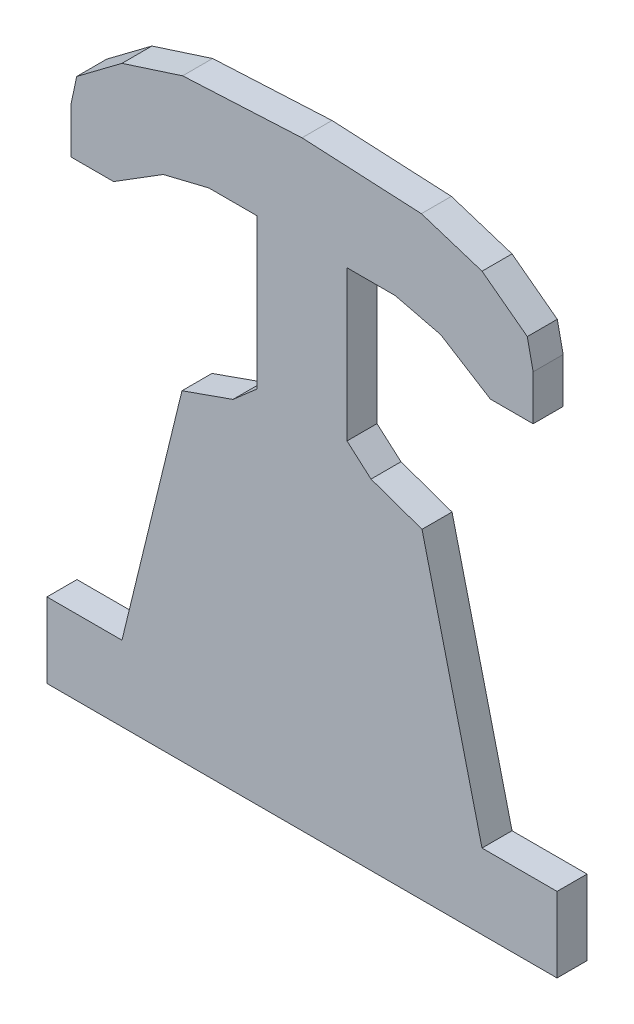
SolidWorks part; units mm, degrees
ref_plane "Front Plane" through (0, 0, 0) normal (0, 0, 1) x (1, 0, 0)
ref_plane "Top Plane" through (0, 0, 0) normal (0, 1, 0) x (1, 0, 0)
ref_plane "Right Plane" through (0, 0, 0) normal (1, 0, 0) x (0, 0, -1)
sketch "Sketch1" plane through (0, 0, 0) normal (0, 0, 1) x (1, 0, 0)
  line L0 (0, -7.1406) -> (0, -46212.8524) construction
  line L1 (40, 107) -> (23, 113)
  line L2 (23, 113) -> (15, 120)
  line L3 (-85, 0) -> (85, 0)
  line L4 (85, 0) -> (85, 25)
  line L5 (15, 170) -> (31.0558, 170)
  line L6 (85, 25) -> (60, 25)
  line L7 (60, 25) -> (40, 107)
  line L8 (31.0558, 170) -> (46.2253, 166.2913)
  line L9 (15, 120) -> (15, 170)
  line L10 (46.2253, 166.2913) -> (62.7938, 155.9714)
  line L11 (0, 200) -> (39.7871, 198)
  line L12 (39.7871, 198) -> (60, 191.5)
  line L13 (60, 191.5) -> (75.0854, 180.1714)
  line L14 (75.0854, 180.1714) -> (77.0338, 170.9714)
  line L15 (77.0338, 170.9714) -> (77.0338, 155.9714)
  line L16 (77.0338, 155.9714) -> (62.7938, 155.9714)
  line L17 (-77.0338, 155.9714) -> (-62.7938, 155.9714)
  line L18 (-77.0338, 170.9714) -> (-77.0338, 155.9714)
  line L19 (-75.0854, 180.1714) -> (-77.0338, 170.9714)
  line L20 (-60, 191.5) -> (-75.0854, 180.1714)
  line L21 (-39.7871, 198) -> (-60, 191.5)
  line L22 (0, 200) -> (-39.7871, 198)
  line L23 (-46.2253, 166.2913) -> (-62.7938, 155.9714)
  line L24 (-15, 120) -> (-15, 170)
  line L25 (-31.0558, 170) -> (-46.2253, 166.2913)
  line L26 (-60, 25) -> (-40, 107)
  line L27 (-85, 25) -> (-60, 25)
  line L28 (-15, 170) -> (-31.0558, 170)
  line L29 (-85, 0) -> (-85, 25)
  line L30 (-23, 113) -> (-15, 120)
  line L31 (-40, 107) -> (-23, 113)
  point P34 (0, 0)
  dimension "D1" = 25
  dimension "D2" = 85
  dimension "D3" = 15
  dimension "D4" = 120
  dimension "D5" = 25
  dimension "D6" = 13
  dimension "D7" = 40
  dimension "D8" = 7
  dimension "D9" = 8
  dimension "D10" = 50
  dimension "D11" = 30
  dimension "D12" = 2
  dimension "D13" = 6.5
  dimension "D14" = 11.3286
  dimension "D15" = 9.2
  dimension "D16" = 15
  dimension "D17" = 20.2129
  dimension "D18" = 39.7871
  dimension "D19" = 15.0854
  dimension "D20" = 15.1695
  dimension "D21" = 16.5686
  dimension "D22" = 10.3199
  dimension "D23" = 1.9484
  dimension "D24" = 16.0558
extrude "Boss-Extrude1" add sketch "Sketch1" along normal blind 10
